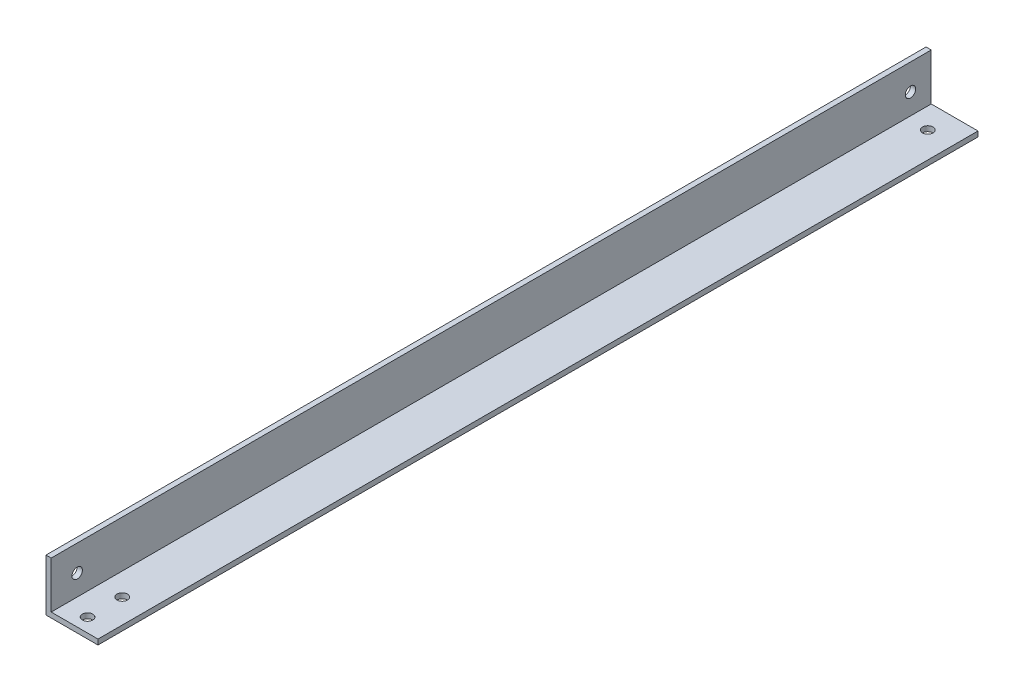
SolidWorks part; units mm, degrees
ref_plane "Plan de face" through (0, 0, 0) normal (0, 0, 1) x (1, 0, 0)
ref_plane "Plan de dessus" through (0, 0, 0) normal (0, 1, 0) x (1, 0, 0)
ref_plane "Plan de droite" through (0, 0, 0) normal (1, 0, 0) x (0, 0, -1)
sketch "Esquisse1" plane through (0, 0, 0) normal (0, 0, 1) x (1, 0, 0)
  line L0 (-21.2354, -5.6274) -> (-21.2354, -20.6274)
  line L1 (-21.2354, -20.6274) -> (-6.2354, -20.6274)
  line L2 (-6.2354, -20.6274) -> (-6.2354, -19.1274)
  line L3 (-6.2354, -19.1274) -> (-19.7354, -19.1274)
  line L4 (-19.7354, -19.1274) -> (-19.7354, -5.6274)
  line L5 (-19.7354, -5.6274) -> (-21.2354, -5.6274)
  dimension "D1" = 1.5
  dimension "D2" = 1.5
  dimension "D3" = 15
  dimension "D4" = 15
extrude "Extrusion1" add sketch "Esquisse1" along normal blind 254
sketch "Esquisse2" plane through (0, -19.1274, 0) normal (0, 1, 0) x (-1, 0, 0)
  line L0 (6.2354, 0) -> (19.7354, 0) construction
  line L1 (6.2354, 254) -> (6.2354, 0) construction
  line L2 (6.2354, 254) -> (19.7354, 254) construction
  line L3 (13.2354, 240) -> (13.2354, 250) construction
  line L4 (21.2354, 254) -> (21.2354, 0) construction
  circle A0 centre (13.7354, 7) radius 1.5
  circle A1 centre (13.2354, 250) radius 1.5
  circle A2 centre (13.2354, 240) radius 1.5
  dimension "D1" = 7
  dimension "D3" = 8
  dimension "D5" = 10
  dimension "D2" = 7.5
  dimension "D4" = 4
extrude "Extrusion2" cut sketch "Esquisse2" against normal blind 186
sketch "Esquisse3" plane through (-19.7354, 0, 0) normal (1, 0, 0) x (0, 0, -1)
  line L0 (0, -19.1274) -> (0, -5.6274) construction
  line L1 (-254, -5.6274) -> (0, -5.6274) construction
  line L2 (-254, -19.1274) -> (-254, -5.6274) construction
  circle A0 centre (-6, -13.1274) radius 1.5
  circle A1 centre (-246.5, -13.1274) radius 1.5
  dimension "D1" = 6
  dimension "D3" = 7.5
  dimension "D2" = 7.5
  dimension "D4" = 7.5
extrude "Extrusion3" cut sketch "Esquisse3" against normal blind 186
